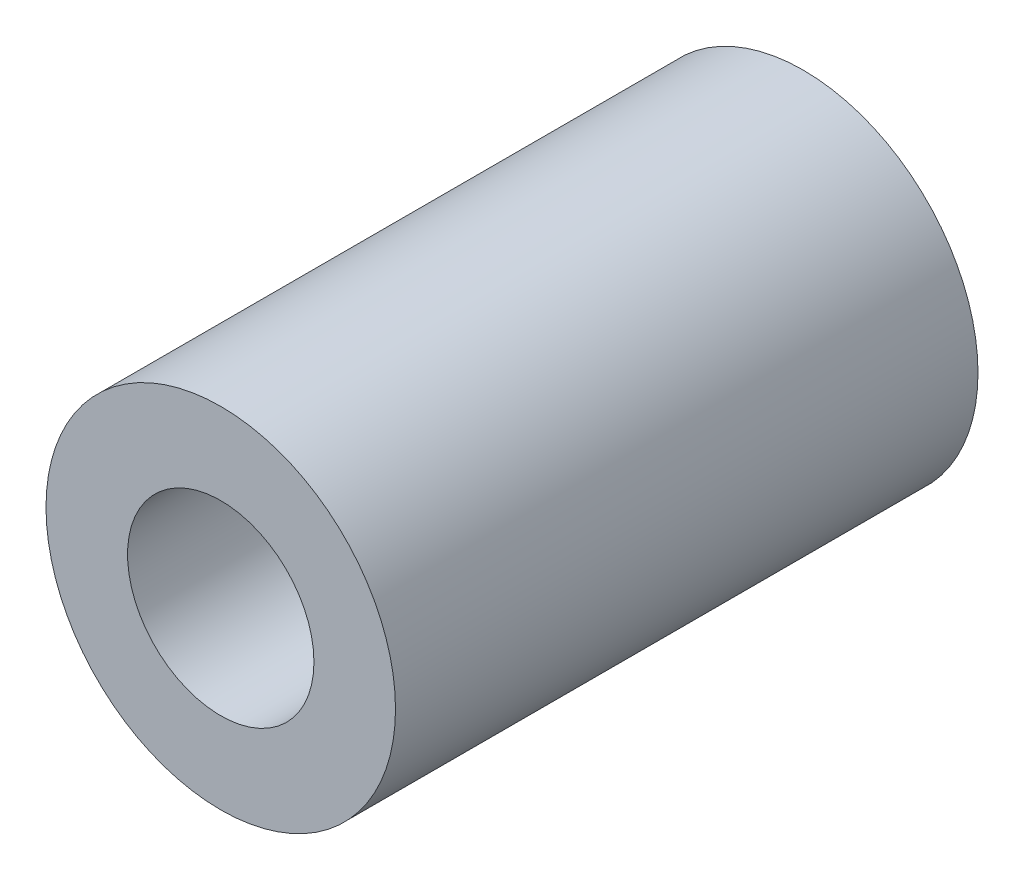
SolidWorks part; units mm, degrees
ref_plane "Front Plane" through (0, 0, 0) normal (0, 0, 1) x (1, 0, 0)
ref_plane "Top Plane" through (0, 0, 0) normal (0, 1, 0) x (1, 0, 0)
ref_plane "Right Plane" through (0, 0, 0) normal (1, 0, 0) x (0, 0, -1)
sketch "Sketch1" plane through (0, 0, 0) normal (0, 0, 1) x (1, 0, 0)
  circle A0 centre (0, 0) radius 2.54
  circle A1 centre (0, 0) radius 4.7625
  dimension "D1" = 5.08
  dimension "D2" = 9.525
extrude "Boss-Extrude1" add sketch "Sketch1" along normal blind 15.875
